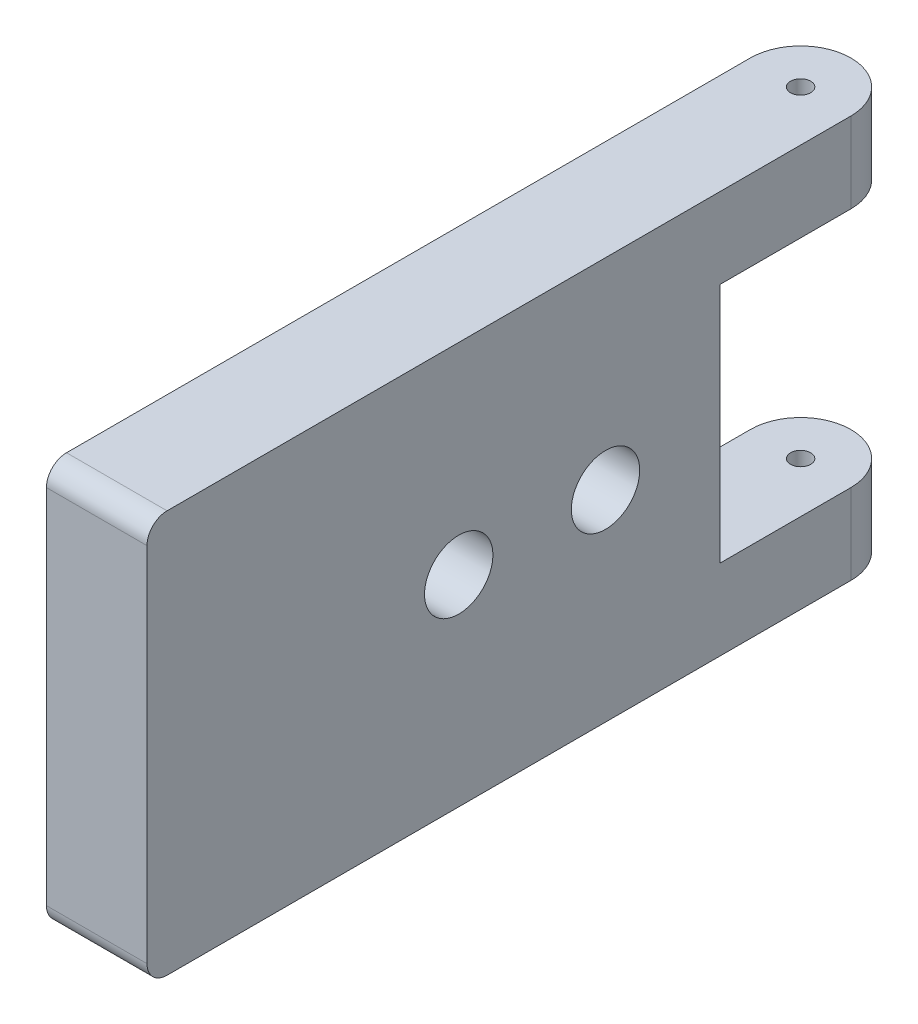
SolidWorks part; units mm, degrees
ref_plane "Front Plane" through (0, 0, 0) normal (0, 0, 1) x (1, 0, 0)
ref_plane "Top Plane" through (0, 0, 0) normal (0, 1, 0) x (1, 0, 0)
ref_plane "Right Plane" through (0, 0, 0) normal (1, 0, 0) x (0, 0, -1)
sketch "SketchSide" plane through (0, 0, 0) normal (0, 1, 0) x (1, 0, 0)
  line L0 (-2.5, -35) -> (2.5, -35)
  line L1 (2.5, -35) -> (2.5, 0)
  line L2 (-2.5, -35) -> (-2.5, 0)
  arc A0 (2.5, 0) -> (-2.5, 0) centre (0, 0) ccw
  circle A1 centre (0, 0) radius 0.5
  dimension "D1" = 5
  dimension "D2" = 2.5
  dimension "D3" = 35
extrude "BossExtrudeSide" add sketch "SketchSide" along normal blind 20
sketch "SketchSensorHoles" plane through (0, 0, 0) normal (1, 0, 0) x (0, 0, -1)
  line L0 (0, 20) -> (0, 0) construction
  line L1 (0, 0) -> (-35, 0) construction
  circle A0 centre (-12.2, 10) radius 1.5 construction
  circle A1 centre (-19.5, 10) radius 1.5 construction
  circle A2 centre (-12.2, 10) radius 1.5
  circle A3 centre (-12.2, 10) radius 1.5
  point P9 (-12.2, 10)
  point P10 (-19.5, 10)
  dimension "D1" = 3
  dimension "D2" = 3
  dimension "D3" = 7.3
  dimension "D4" = 12.2
  dimension "D5" = 10
sketch "SketchDistalRoom" plane through (0, 0, 0) normal (1, 0, 0) x (0, 0, -1)
  line L0 (2.5, 16) -> (-6.5, 16)
  line L1 (2.5, 0) -> (2.5, 20) construction
  line L2 (-6.5, 16) -> (-6.5, 4)
  line L3 (-6.5, 4) -> (2.5, 4)
  line L4 (2.5, 4) -> (2.5, 16)
  line L5 (2.5, 20) -> (0, 20) construction
  dimension "D1" = 12
  dimension "D2" = 4
  dimension "D3" = 9
extrude "CutExtrudeDistalRoom" cut sketch "SketchDistalRoom" against normal through all both and the other way through all
fillet "FilletButtom" radius 1 2 edges at (0, 20, 35) (0, 0, 35)
sketch "SketchSensorHolesCenter" plane through (-2.5, 0, 0) normal (-1, 0, 0) x (0, 0, 1)
  point P0 (12.2, 10)
  point P1 (19.5, 10)
hole_wizard "CSKM3FlatHeadMachineScrew" positions "3DSketchSensorHolesCenter" profile "SketchFlatHead" countersink size "M3" standard "ANSI Metric" end condition through all
sketch3d "3DSketchSensorHolesCenter"
  point P0 (-2.5, 10, 12.2)
  point P3 (-2.5, 10, 19.5)
sketch "SketchFlatHead" plane through (-2.5, 10, 12.2) normal (0, 1, 0) x (0, 0, 1)
  line L0 (0, 0) -> (0, 5)
  line L1 (0, 5) -> (1.7, 5)
  line L2 (1.7, 5) -> (1.7, 1.45)
  line L3 (1.7, 1.45) -> (3.15, 0)
  line L5 (3.15, 0) -> (0, 0)
  line L6 (-1.7, 1.45) -> (-3.15, 0) construction
  line L11 (0, -6.35) -> (0, 107.95) construction
  dimension "Thru Hole Dia." = 3.4
  dimension "Thru Hole Depth" = 5
  dimension "Near C'Sink Dia." = 6.3
  dimension "Near C'Sink Angle" = 90
